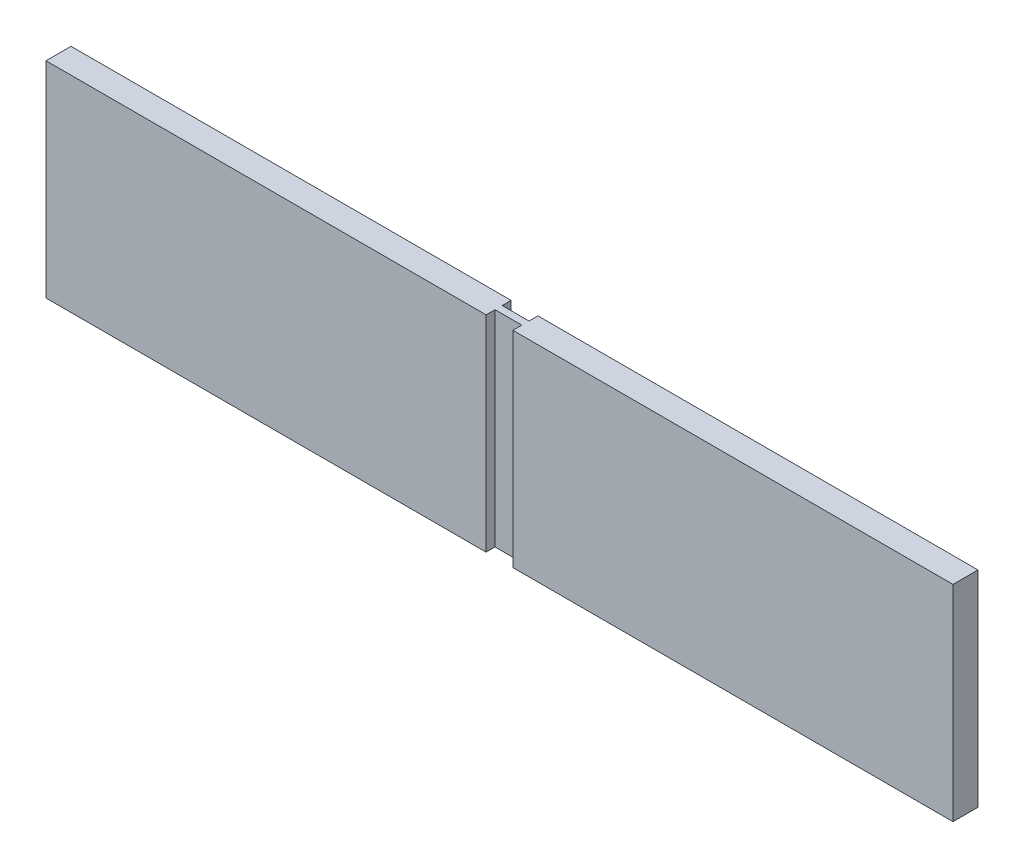
SolidWorks part; units mm, degrees
ref_plane "Front Plane" through (0, 0, 0) normal (0, 0, 1) x (1, 0, 0)
ref_plane "Top Plane" through (0, 0, 0) normal (0, 1, 0) x (1, 0, 0)
ref_plane "Right Plane" through (0, 0, 0) normal (1, 0, 0) x (0, 0, -1)
sketch "Sketch1" plane through (0, 0, 0) normal (0, 0, 1) x (1, 0, 0)
  line L1 (0, 0) -> (101.5, 0)
  line L2 (0, 0) -> (0, 23)
  line L3 (0, 23) -> (101.5, 23)
  line L4 (101.5, 0) -> (101.5, 23)
  dimension "D1" = 23
  dimension "D2" = 101.5
extrude "Boss-Extrude1" add sketch "Sketch1" along normal blind 2.8
sketch "Sketch2" plane through (0, 23, 0) normal (0, 1, 0) x (1, 0, 0)
  line L0 (101.5, 0) -> (0, 0) construction
  line L1 (49.25, 0) -> (52.25, 0)
  line L2 (49.25, 0) -> (49.25, -1)
  line L3 (49.25, -1) -> (52.25, -1)
  line L4 (52.25, 0) -> (52.25, -1)
  line L5 (0, -2.8) -> (0, 0) construction
  line L7 (101.5, -2.8) -> (101.5, 0) construction
  point P6 (0, -1.4)
  dimension "D1" = 49.25
  dimension "D2" = 49.25
  dimension "D3" = 1
extrude "Cut-Extrude1" cut sketch "Sketch2" against normal blind 33
sketch "Sketch3" plane through (0, 23, 0) normal (0, 1, 0) x (1, 0, 0)
  line L0 (101.5, -2.8) -> (0, -2.8) construction
  line L1 (49.25, -2.8) -> (52.25, -2.8)
  line L2 (49.25, -2.8) -> (49.25, -1.8)
  line L3 (49.25, -1.8) -> (52.25, -1.8)
  line L4 (52.25, -2.8) -> (52.25, -1.8)
  line L5 (101.5, -2.8) -> (101.5, 0) construction
  line L6 (0, -2.8) -> (0, 0) construction
  dimension "D1" = 1
  dimension "D2" = 49.25
  dimension "D3" = 49.25
extrude "Cut-Extrude2" cut sketch "Sketch3" against normal blind 33
